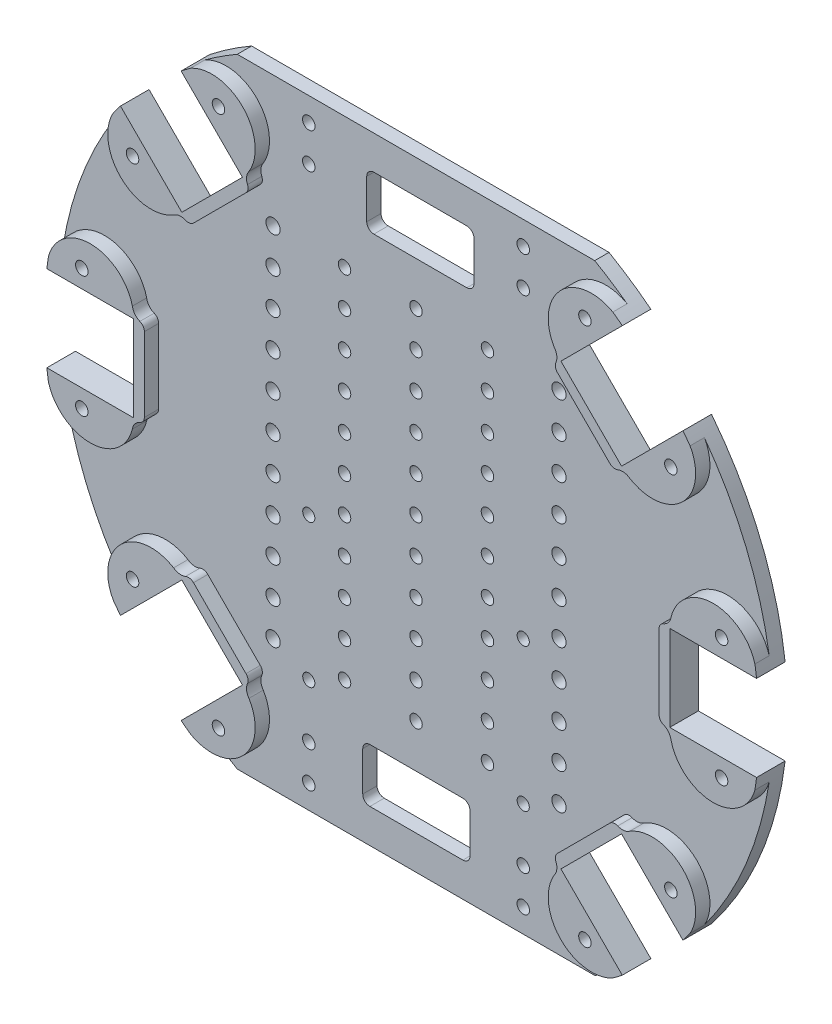
SolidWorks part; units mm, degrees
ref_plane "Front Plane" through (0, 0, 0) normal (0, 0, 1) x (1, 0, 0)
ref_plane "Top Plane" through (0, 0, 0) normal (0, 1, 0) x (1, 0, 0)
ref_plane "Right Plane" through (0, 0, 0) normal (1, 0, 0) x (0, 0, -1)
sketch "Sketch1" plane through (0, 0, 0) normal (0, 0, 1) x (1, 0, 0)
  line L0 (0, 0) -> (0, 100) construction
  line L5 (44.5477, 61.5183) -> (61.7144, 78.685)
  line L6 (44.5477, 61.5183) -> (61.5183, 44.5477)
  line L7 (-12, 75) -> (12, 75) construction
  line L8 (-12, 75) -> (-12, 99.2774) construction
  line L9 (12, 75) -> (12, 99.2774) construction
  line L10 (-17, 89.5) -> (17, 89.5) construction
  line L11 (61.5183, 44.5477) -> (78.685, 61.7144)
  line L12 (75, 12) -> (99.2774, 12)
  line L13 (75, 12) -> (75, -12)
  line L14 (75, -12) -> (99.2774, -12)
  line L15 (61.5183, -44.5477) -> (78.685, -61.7144)
  line L16 (61.5183, -44.5477) -> (44.5477, -61.5183)
  line L17 (44.5477, -61.5183) -> (61.7144, -78.685)
  line L18 (12, -75) -> (12, -99.2774) construction
  line L19 (12, -75) -> (-12, -75) construction
  line L20 (-12, -75) -> (-12, -99.2774) construction
  line L21 (-44.5477, -61.5183) -> (-61.7144, -78.685)
  line L22 (-44.5477, -61.5183) -> (-61.5183, -44.5477)
  line L23 (-61.5183, -44.5477) -> (-78.685, -61.7144)
  line L24 (-75, -12) -> (-99.2774, -12)
  line L25 (-75, -12) -> (-75, 12)
  line L26 (-75, 12) -> (-99.2774, 12)
  line L27 (-61.5183, 44.5477) -> (-78.685, 61.7144)
  line L28 (-61.5183, 44.5477) -> (-44.5477, 61.5183)
  line L29 (-44.5477, 61.5183) -> (-61.7144, 78.685)
  circle A1 centre (0, 0) radius 100
  circle A2 centre (-17, 89.5) radius 1.75 construction
  circle A3 centre (17, 89.5) radius 1.75 construction
  circle A4 centre (51.2652, 75.3069) radius 1.75
  circle A5 centre (75.3069, 51.2652) radius 1.75
  circle A6 centre (89.5, 17) radius 1.75
  circle A7 centre (89.5, -17) radius 1.75
  circle A8 centre (75.3069, -51.2652) radius 1.75
  circle A9 centre (51.2652, -75.3069) radius 1.75
  circle A10 centre (17, -89.5) radius 1.75 construction
  circle A11 centre (-17, -89.5) radius 1.75 construction
  circle A12 centre (-51.2652, -75.3069) radius 1.75
  circle A13 centre (-75.3069, -51.2652) radius 1.75
  circle A14 centre (-89.5, -17) radius 1.75
  circle A15 centre (-89.5, 17) radius 1.75
  circle A16 centre (-75.3069, 51.2652) radius 1.75
  circle A17 centre (-51.2652, 75.3069) radius 1.75
  point P2 (0, 89.5)
  point P4 (0, 75)
  point P12 (0, 75)
  point P19 (0, 89.5)
  dimension "150" = 200
  dimension "D7" = 3.5
  dimension "D2" = 25
  dimension "D3" = 8
  dimension "D4" = 24
  dimension "D5" = 14.5
  dimension "D6" = 34
extrude "Boss-Extrude1" add sketch "Sketch1" along normal blind 4 contours L12 A1 L11 L6 L5 L29 L28 L27 L26 L25 L24 L23 L22 L21 L17 L16 L15 L14 L13 A15 A14 A9 A8 A5 A4 A6 A7 A12 A13 A16 A17
sketch "Sketch2" plane through (0, 0, 4) normal (0, 0, 1) x (1, 0, 0)
  line L0 (0, 35) -> (0, -35) construction
  line L1 (-35, 35) -> (35, 35) construction
  line L2 (-35, 35) -> (-35, -35) construction
  line L3 (-35, -35) -> (35, -35) construction
  line L4 (35, 35) -> (35, -35) construction
  line L5 (-35, 35) -> (35, -35) construction
  line L6 (-35, -35) -> (35, 35) construction
  line L7 (0, 35) -> (0, 80)
  line L8 (-30, -15) -> (30, -15) construction
  line L9 (-30, -15) -> (-30, -55) construction
  line L10 (-30, -55) -> (30, -55) construction
  line L11 (30, -15) -> (30, -55) construction
  line L12 (-30, -15) -> (30, -55) construction
  line L13 (-30, -55) -> (30, -15) construction
  line L14 (-30, 80) -> (30, 80)
  line L15 (0, -55) -> (0, -80)
  line L16 (30, -80) -> (-30, -80)
  line L17 (0, 0) -> (-40, 0) construction
  line L18 (0, 0) -> (40, 0) construction
  line L19 (0, 10) -> (-40, 10)
  line L20 (0, 10) -> (40, 10)
  line L21 (0, 20) -> (-40, 20)
  line L22 (0, 20) -> (40, 20)
  line L23 (0, 30) -> (-40, 30)
  line L24 (0, 30) -> (40, 30)
  line L25 (0, 40) -> (-40, 40)
  line L26 (0, 40) -> (40, 40)
  line L27 (0, 50) -> (-40, 50)
  line L28 (0, 50) -> (40, 50)
  line L29 (0, -10) -> (40, -10)
  line L30 (0, -10) -> (-40, -10)
  line L31 (0, -20) -> (40, -20)
  line L32 (0, -20) -> (-40, -20)
  line L33 (0, -30) -> (40, -30)
  line L34 (0, -30) -> (-40, -30)
  line L35 (0, -40) -> (40, -40)
  line L36 (0, -40) -> (-40, -40)
  line L37 (0, -50) -> (40, -50)
  line L38 (0, -50) -> (-40, -50)
  line L39 (30, -70) -> (-30, -70)
  line L40 (-30, 70) -> (30, 70)
  circle A0 centre (0, 0) radius 100
  circle A1 centre (-30, -55) radius 1.7
  circle A2 centre (-30, -15) radius 1.7
  circle A3 centre (30, -55) radius 1.7
  circle A4 centre (30, -15) radius 1.7
  circle A5 centre (-30, 80) radius 1.75
  circle A6 centre (30, 80) radius 1.75
  circle A7 centre (-30, -80) radius 1.75
  circle A8 centre (30, -80) radius 1.75
  circle A9 centre (-40, 0) radius 2
  circle A10 centre (-20, 0) radius 1.75
  circle A11 centre (0, 0) radius 1.75
  circle A12 centre (40, 0) radius 2
  circle A13 centre (20, 0) radius 1.75
  circle A14 centre (20, 10) radius 1.75
  circle A15 centre (40, 10) radius 2
  circle A16 centre (-20, 10) radius 1.75
  circle A17 centre (-40, 10) radius 2
  circle A18 centre (0, 10) radius 1.75
  circle A19 centre (20, 20) radius 1.75
  circle A20 centre (40, 20) radius 2
  circle A21 centre (-20, 20) radius 1.75
  circle A22 centre (-40, 20) radius 2
  circle A23 centre (0, 20) radius 1.75
  circle A24 centre (20, 30) radius 1.75
  circle A25 centre (40, 30) radius 2
  circle A26 centre (-20, 30) radius 1.75
  circle A27 centre (-40, 30) radius 2
  circle A28 centre (0, 30) radius 1.75
  circle A29 centre (20, 40) radius 1.75
  circle A30 centre (40, 40) radius 2
  circle A31 centre (-20, 40) radius 1.75
  circle A32 centre (-40, 40) radius 2
  circle A33 centre (0, 40) radius 1.75
  circle A34 centre (20, 50) radius 1.75
  circle A35 centre (40, 50) radius 2
  circle A36 centre (-20, 50) radius 1.75
  circle A37 centre (-40, 50) radius 2
  circle A38 centre (0, 50) radius 1.75
  circle A39 centre (40, -10) radius 2
  circle A40 centre (0, -10) radius 1.75
  circle A41 centre (20, -10) radius 1.75
  circle A42 centre (-20, -10) radius 1.75
  circle A43 centre (-40, -10) radius 2
  circle A44 centre (40, -20) radius 2
  circle A45 centre (0, -20) radius 1.75
  circle A46 centre (20, -20) radius 1.75
  circle A47 centre (-20, -20) radius 1.75
  circle A48 centre (-40, -20) radius 2
  circle A49 centre (40, -30) radius 2
  circle A50 centre (0, -30) radius 1.75
  circle A51 centre (20, -30) radius 1.75
  circle A52 centre (-20, -30) radius 1.75
  circle A53 centre (-40, -30) radius 2
  circle A54 centre (40, -40) radius 2
  circle A55 centre (0, -40) radius 1.75
  circle A56 centre (20, -40) radius 1.75
  circle A57 centre (-20, -40) radius 1.75
  circle A58 centre (-40, -40) radius 2
  circle A59 centre (40, -50) radius 2
  circle A60 centre (0, -50) radius 1.75
  circle A61 centre (20, -50) radius 1.75
  circle A62 centre (-20, -50) radius 1.75
  circle A63 centre (-40, -50) radius 2
  circle A64 centre (30, -70) radius 1.75
  circle A65 centre (-30, -70) radius 1.75
  circle A66 centre (-30, 70) radius 1.75
  circle A67 centre (30, 70) radius 1.75
  point P10 (0, 0)
  point P23 (0, 80)
  point P30 (0, -80)
  dimension "D1" = 200
  dimension "D6" = 3.4
  dimension "D9" = 3.5
  dimension "D10" = 3.5
  dimension "D13" = 3.5
  dimension "D14" = 3.5
  dimension "D16" = 4
  dimension "D17" = 3.5
  dimension "D18" = 3.5
  dimension "D2" = 70
  dimension "D3" = 70
  dimension "D4" = 40
  dimension "D5" = 60
  dimension "D7" = 45
  dimension "D8" = 60
  dimension "D11" = 25
  dimension "D12" = 60
  dimension "D15" = 40
  dimension "D19" = 6
  dimension "D20" = 6
  dimension "D21" = 2
  dimension "D22" = 2
extrude "Cut-Extrude1" cut sketch "Sketch2" against normal blind 10
sketch "Sketch3" plane through (0, 0, 4) normal (0, 0, 1) x (1, 0, 0)
  line L0 (-78.685, 61.7144) -> (-61.5183, 44.5477)
  line L1 (-61.5183, 44.5477) -> (-44.5477, 61.5183)
  line L2 (-44.5477, 61.5183) -> (-61.7144, 78.685)
  line L3 (-58.255, 43.5684) -> (-43.5684, 58.255)
  line L4 (-53.033, 53.033) -> (-50.9117, 50.9117)
  line L5 (-10.385, 72) -> (10.385, 72)
  line L6 (-12, 75) -> (12, 75)
  line L7 (-12, 99.2774) -> (-12, 75)
  line L8 (12, 75) -> (12, 99.2774)
  line L9 (43.5684, 58.255) -> (58.255, 43.5684)
  line L10 (44.5477, 61.5183) -> (61.5183, 44.5477)
  line L11 (61.7144, 78.685) -> (44.5477, 61.5183)
  line L12 (61.5183, 44.5477) -> (78.685, 61.7144)
  line L13 (72, 10.385) -> (72, -10.385)
  line L14 (75, 12) -> (75, -12)
  line L15 (99.2774, 12) -> (75, 12)
  line L16 (75, -12) -> (99.2774, -12)
  line L17 (58.255, -43.5684) -> (43.5684, -58.255)
  line L18 (61.5183, -44.5477) -> (44.5477, -61.5183)
  line L19 (78.685, -61.7144) -> (61.5183, -44.5477)
  line L20 (44.5477, -61.5183) -> (61.7144, -78.685)
  line L21 (10.385, -72) -> (-10.385, -72)
  line L22 (12, -75) -> (-12, -75)
  line L23 (12, -99.2774) -> (12, -75)
  line L24 (-12, -75) -> (-12, -99.2774)
  line L25 (-43.5684, -58.255) -> (-58.255, -43.5684)
  line L26 (-44.5477, -61.5183) -> (-61.5183, -44.5477)
  line L27 (-61.7144, -78.685) -> (-44.5477, -61.5183)
  line L28 (-61.5183, -44.5477) -> (-78.685, -61.7144)
  line L29 (-72, -10.385) -> (-72, 10.385)
  line L30 (-75, -12) -> (-75, 12)
  line L31 (-99.2774, -12) -> (-75, -12)
  line L32 (-75, 12) -> (-99.2774, 12)
  arc A1 (-12.2421, 73.2574) -> (-10.385, 72) centre (-10.385, 74) ccw
  circle A2 centre (0, 0) radius 100
  arc A3 (-61.5183, 44.5477) -> (-78.685, 61.7144) centre (-70.1016, 53.1311) cw
  arc A4 (-61.7144, 78.685) -> (-44.5477, 61.5183) centre (-53.1311, 70.1016) cw
  circle A5 centre (-51.2652, 75.3069) radius 1.75
  circle A6 centre (-75.3069, 51.2652) radius 1.75
  arc A7 (-43.1444, 60.4573) -> (-42.7452, 63.8182) centre (-40.0316, 61.7918) cw
  arc A8 (-60.4573, 43.1444) -> (-63.8182, 42.7452) centre (-61.7918, 40.0316) ccw
  arc A9 (-60.4573, 43.1444) -> (-58.255, 43.5684) centre (-59.6692, 44.9826) ccw
  arc A10 (-43.1444, 60.4573) -> (-43.5684, 58.255) centre (-44.9826, 59.6692) cw
  arc A11 (-12.2421, 73.2574) -> (-14.9009, 75.3517) centre (-15.3867, 72) ccw
  arc A12 (-12, 75) -> (-12, 99.2774) centre (-12, 87.1387) cw
  circle A13 centre (-17, 89.5) radius 1.75
  circle A14 centre (17, 89.5) radius 1.75
  arc A15 (12, 99.2774) -> (12, 75) centre (12, 87.1387) cw
  arc A16 (12.2421, 73.2574) -> (14.9009, 75.3517) centre (15.3867, 72) cw
  arc A17 (12.2421, 73.2574) -> (10.385, 72) centre (10.385, 74) cw
  arc A18 (43.1444, 60.4573) -> (43.5684, 58.255) centre (44.9826, 59.6692) ccw
  arc A19 (43.1444, 60.4573) -> (42.7452, 63.8182) centre (40.0316, 61.7918) ccw
  arc A20 (44.5477, 61.5183) -> (61.7144, 78.685) centre (53.1311, 70.1016) cw
  circle A21 centre (51.2652, 75.3069) radius 1.75
  circle A22 centre (75.3069, 51.2652) radius 1.75
  arc A23 (78.685, 61.7144) -> (61.5183, 44.5477) centre (70.1016, 53.1311) cw
  arc A24 (60.4573, 43.1444) -> (63.8182, 42.7452) centre (61.7918, 40.0316) cw
  arc A25 (60.4573, 43.1444) -> (58.255, 43.5684) centre (59.6692, 44.9826) cw
  arc A26 (73.2574, 12.2421) -> (72, 10.385) centre (74, 10.385) ccw
  arc A27 (73.2574, 12.2421) -> (75.3517, 14.9009) centre (72, 15.3867) ccw
  arc A28 (75, 12) -> (99.2774, 12) centre (87.1387, 12) cw
  circle A29 centre (89.5, 17) radius 1.75
  circle A30 centre (89.5, -17) radius 1.75
  arc A31 (99.2774, -12) -> (75, -12) centre (87.1387, -12) cw
  arc A32 (73.2574, -12.2421) -> (75.3517, -14.9009) centre (72, -15.3867) cw
  arc A33 (73.2574, -12.2421) -> (72, -10.385) centre (74, -10.385) cw
  arc A34 (60.4573, -43.1444) -> (58.255, -43.5684) centre (59.6692, -44.9826) ccw
  arc A35 (60.4573, -43.1444) -> (63.8182, -42.7452) centre (61.7918, -40.0316) ccw
  arc A36 (61.5183, -44.5477) -> (78.685, -61.7144) centre (70.1016, -53.1311) cw
  circle A37 centre (75.3069, -51.2652) radius 1.75
  circle A38 centre (51.2652, -75.3069) radius 1.75
  arc A39 (61.7144, -78.685) -> (44.5477, -61.5183) centre (53.1311, -70.1016) cw
  arc A40 (43.1444, -60.4573) -> (42.7452, -63.8182) centre (40.0316, -61.7918) cw
  arc A41 (43.1444, -60.4573) -> (43.5684, -58.255) centre (44.9826, -59.6692) cw
  arc A42 (12.2421, -73.2574) -> (10.385, -72) centre (10.385, -74) ccw
  arc A43 (12.2421, -73.2574) -> (14.9009, -75.3517) centre (15.3867, -72) ccw
  arc A44 (12, -75) -> (12, -99.2774) centre (12, -87.1387) cw
  circle A45 centre (17, -89.5) radius 1.75
  circle A46 centre (-17, -89.5) radius 1.75
  arc A47 (-12, -99.2774) -> (-12, -75) centre (-12, -87.1387) cw
  arc A48 (-12.2421, -73.2574) -> (-14.9009, -75.3517) centre (-15.3867, -72) cw
  arc A49 (-12.2421, -73.2574) -> (-10.385, -72) centre (-10.385, -74) cw
  arc A50 (-43.1444, -60.4573) -> (-43.5684, -58.255) centre (-44.9826, -59.6692) ccw
  arc A51 (-43.1444, -60.4573) -> (-42.7452, -63.8182) centre (-40.0316, -61.7918) ccw
  arc A52 (-44.5477, -61.5183) -> (-61.7144, -78.685) centre (-53.1311, -70.1016) cw
  circle A53 centre (-51.2652, -75.3069) radius 1.75
  circle A54 centre (-75.3069, -51.2652) radius 1.75
  arc A55 (-78.685, -61.7144) -> (-61.5183, -44.5477) centre (-70.1016, -53.1311) cw
  arc A56 (-60.4573, -43.1444) -> (-63.8182, -42.7452) centre (-61.7918, -40.0316) cw
  arc A57 (-60.4573, -43.1444) -> (-58.255, -43.5684) centre (-59.6692, -44.9826) cw
  arc A58 (-73.2574, -12.2421) -> (-72, -10.385) centre (-74, -10.385) ccw
  arc A59 (-73.2574, -12.2421) -> (-75.3517, -14.9009) centre (-72, -15.3867) ccw
  arc A60 (-75, -12) -> (-99.2774, -12) centre (-87.1387, -12) cw
  circle A61 centre (-89.5, -17) radius 1.75
  circle A62 centre (-89.5, 17) radius 1.75
  arc A63 (-99.2774, 12) -> (-75, 12) centre (-87.1387, 12) cw
  arc A64 (-73.2574, 12.2421) -> (-75.3517, 14.9009) centre (-72, 15.3867) cw
  arc A65 (-73.2574, 12.2421) -> (-72, 10.385) centre (-74, 10.385) cw
  point P29 (-59.397, 42.4264)
  point P32 (-42.4264, 59.397)
  dimension "D2" = 2
  dimension "D1" = 2
  dimension "D3" = 8
extrude "Boss-Extrude2" add sketch "Sketch3" along normal blind 4 contours A39 A40 A2 L20 A38 | A41 A40 A39 L18 A36 A35 A34 L17 | A36 L19 A2 A35 A37 | A31 A32 A2 L16 A30 | A33 A32 A31 L14 A28 A27 A26 L13 | A28 L15 A2 A27 A29 | A23 A24 A2 L12 A22 | A25 A24 A23 L10 A20 A19 A18 L9 | A20 L11 A2 A19 A21 | A4 A7 A2 L2 A5 | A10 A7 A4 L1 L4 L3 | A8 A9 L3 L4 L1 A3 | A8 A3 L0 A2 A6 | A63 A64 A2 L32 A62 | A65 A64 A63 L30 A60 A59 A58 L29 | A60 L31 A2 A59 A61 | A55 A56 A2 L28 A54 | A57 A56 A55 L26 A52 A51 A50 L25 | A52 L27 A2 A51 A53
sketch "Sketch4" plane through (0, 0, 4) normal (0, 0, 1) x (1, 0, 0)
  line L0 (14.2118, 62.1273) -> (-11.7882, 62.1273)
  line L1 (13.1, -77.0997) -> (-12.9, -77.0997)
  line L2 (15.1, -75.0997) -> (15.1, -64.0997)
  line L3 (13.1, -62.0997) -> (-12.9, -62.0997)
  line L4 (-14.9, -75.0997) -> (-14.9, -64.0997)
  line L5 (15.1, -77.0997) -> (-14.9, -62.0997) construction
  line L6 (15.1, -62.0997) -> (-14.9, -77.0997) construction
  line L7 (16.2118, 64.1273) -> (16.2118, 75.1273)
  line L8 (14.2118, 77.1273) -> (-11.7882, 77.1273)
  line L9 (-13.7882, 64.1273) -> (-13.7882, 75.1273)
  arc A0 (-14.9, -75.0997) -> (-12.9, -77.0997) centre (-12.9, -75.0997) ccw
  arc A1 (-14.9, -64.0997) -> (-12.9, -62.0997) centre (-12.9, -64.0997) cw
  arc A2 (13.1, -62.0997) -> (15.1, -64.0997) centre (13.1, -64.0997) cw
  arc A3 (13.1, -77.0997) -> (15.1, -75.0997) centre (13.1, -75.0997) ccw
  arc A4 (-13.7882, 64.1273) -> (-11.7882, 62.1273) centre (-11.7882, 64.1273) ccw
  arc A5 (-13.7882, 75.1273) -> (-11.7882, 77.1273) centre (-11.7882, 75.1273) cw
  arc A6 (14.2118, 77.1273) -> (16.2118, 75.1273) centre (14.2118, 75.1273) cw
  arc A7 (14.2118, 62.1273) -> (16.2118, 64.1273) centre (14.2118, 64.1273) ccw
  point P0 (0.1, -69.5997)
  dimension "D3" = 2
  dimension "D1" = 15
  dimension "D2" = 30
extrude "Cut-Extrude2" cut sketch "Sketch4" against normal blind 10 contours L1 A3 L2 A2 L3 A1 L4 A0 | L0 A4 L9 A5 L8 A6 L7 A7
sketch "Sketch5" plane through (0, 0, 4) normal (0, 0, 1) x (1, 0, 0)
  line L0 (0, 0) -> (0, -100) construction
  line L1 (50, -86.6025) -> (-50, -86.6025)
  line L2 (0, 0) -> (-100, 0) construction
  line L3 (50, 86.6025) -> (-50, 86.6025)
  circle A0 centre (0, 0) radius 100
  point P7 (0, -86.6025)
  dimension "D1" = 200
  dimension "D2" = 100
extrude "Cut-Extrude3" cut sketch "Sketch5" against normal through all contours L1 A0 | L3 A0
